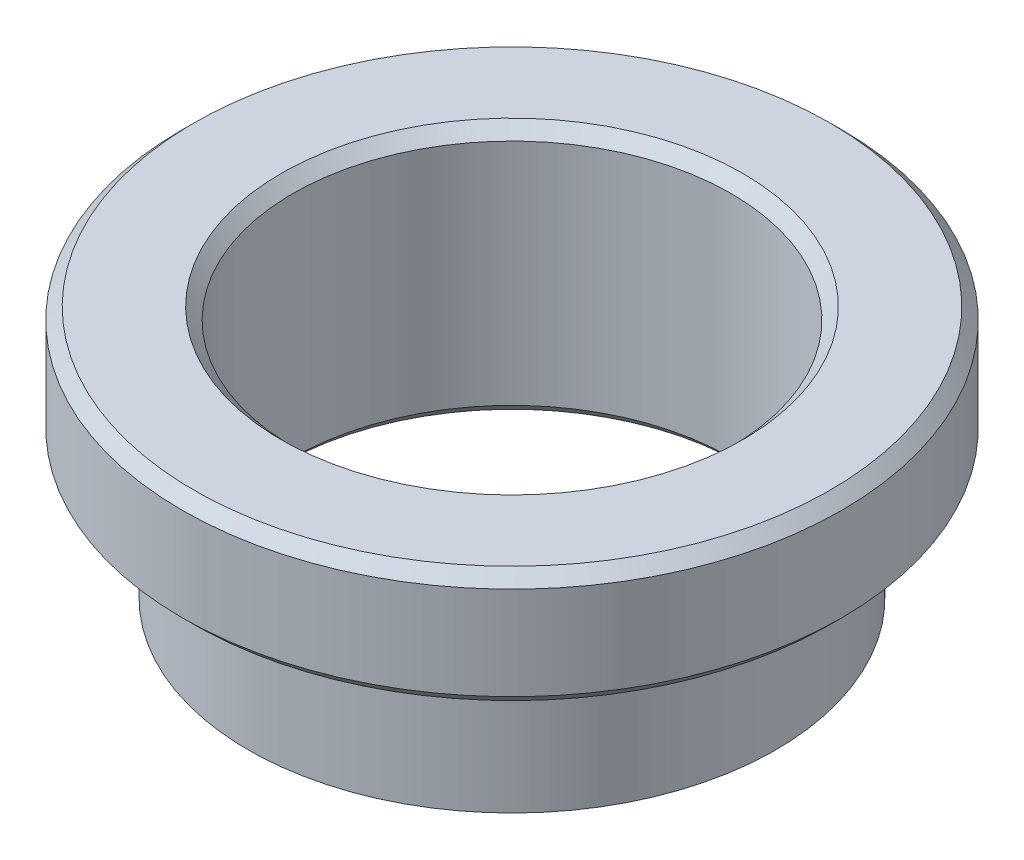
SolidWorks part; units mm, degrees
material "1060 Сплав"
ref_plane "Спереди" through (0, 0, 0) normal (0, 0, 1) x (1, 0, 0)
ref_plane "Сверху" through (0, 0, 0) normal (0, 1, 0) x (1, 0, 0)
ref_plane "Справа" through (0, 0, 0) normal (1, 0, 0) x (0, 0, -1)
sketch "Эскиз2" plane through (0, 0, 0) normal (0, 0, 1) x (1, 0, 0)
  line L0 (6.8, 3.5) -> (8.2, 3.5)
  line L1 (5.95, 0) -> (6.8, 0)
  line L2 (0, 0) -> (0, 6.5)
  line L3 (5.95, 6.5) -> (8.2, 6.5)
  line L4 (8.5, 3.8) -> (8.5, 6.2)
  line L5 (5.65, 0) -> (6.8, 0)
  line L6 (0, 0) -> (0, 3.5)
  line L7 (5.65, 0.3) -> (5.65, 6.2)
  line L8 (6.8, 0) -> (6.8, 3.5)
  line L9 (5.65, 6.2) -> (5.95, 6.5)
  line L10 (8.2, 6.5) -> (8.5, 6.2)
  line L11 (8.2, 3.5) -> (8.5, 3.8)
  line L12 (5.95, 0) -> (5.65, 0.3)
  point P1 (8.5, 6.5)
  point P8 (5.65, 6.5)
  point P9 (8.5, 3.5)
  dimension "D1" = 8.5
  dimension "D2" = 6.8
  dimension "D3" = 3
  dimension "D4" = 6.5
  dimension "D5" = 5.65
revolve "Повернуть1" add sketch "Эскиз2" angle 360 about L2
cosmetic thread "Условное изображение резьбы1" parameters "D2"=14
